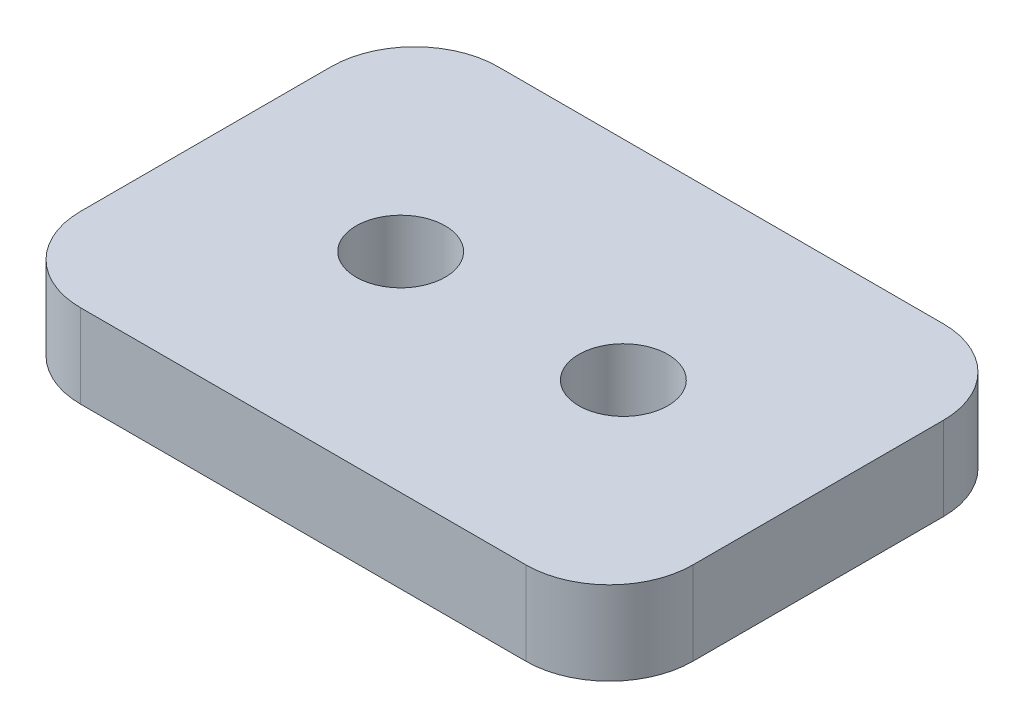
SolidWorks part; units mm, degrees
material "ABS"
ref_plane "前视基准面" through (0, 0, 0) normal (0, 0, 1) x (1, 0, 0)
ref_plane "上视基准面" through (0, 0, 0) normal (0, 1, 0) x (1, 0, 0)
ref_plane "右视基准面" through (0, 0, 0) normal (1, 0, 0) x (0, 0, -1)
other "Configuration Table"
sketch "草图1" plane through (0, 0, 0) normal (0, 1, 0) x (1, 0, 0)
  line L0 (14.4141, 0) -> (-15.5051, 0) construction
  line L1 (-11, -7.5) -> (11, -7.5)
  line L2 (-11, -7.5) -> (-11, 7.5)
  line L3 (-11, 7.5) -> (11, 7.5)
  line L4 (11, -7.5) -> (11, 7.5)
  line L5 (-11, -7.5) -> (11, 7.5) construction
  line L6 (-11, 7.5) -> (11, -7.5) construction
  circle A0 centre (-4, 0) radius 1.6
  circle A1 centre (4, 0) radius 1.6
  point P0 (0, 0)
  dimension "D3" = 3.2
  dimension "D4" = 7
  dimension "D1" = 22
  dimension "D2" = 15
  dimension "D5" = 7
extrude "凸台-拉伸1" add sketch "草图1" along normal blind 3
fillet "圆角1" radius 3 4 edges at (-11, 1.5, 7.5) (-11, 1.5, -7.5) (11, 1.5, -7.5) (11, 1.5, 7.5)
